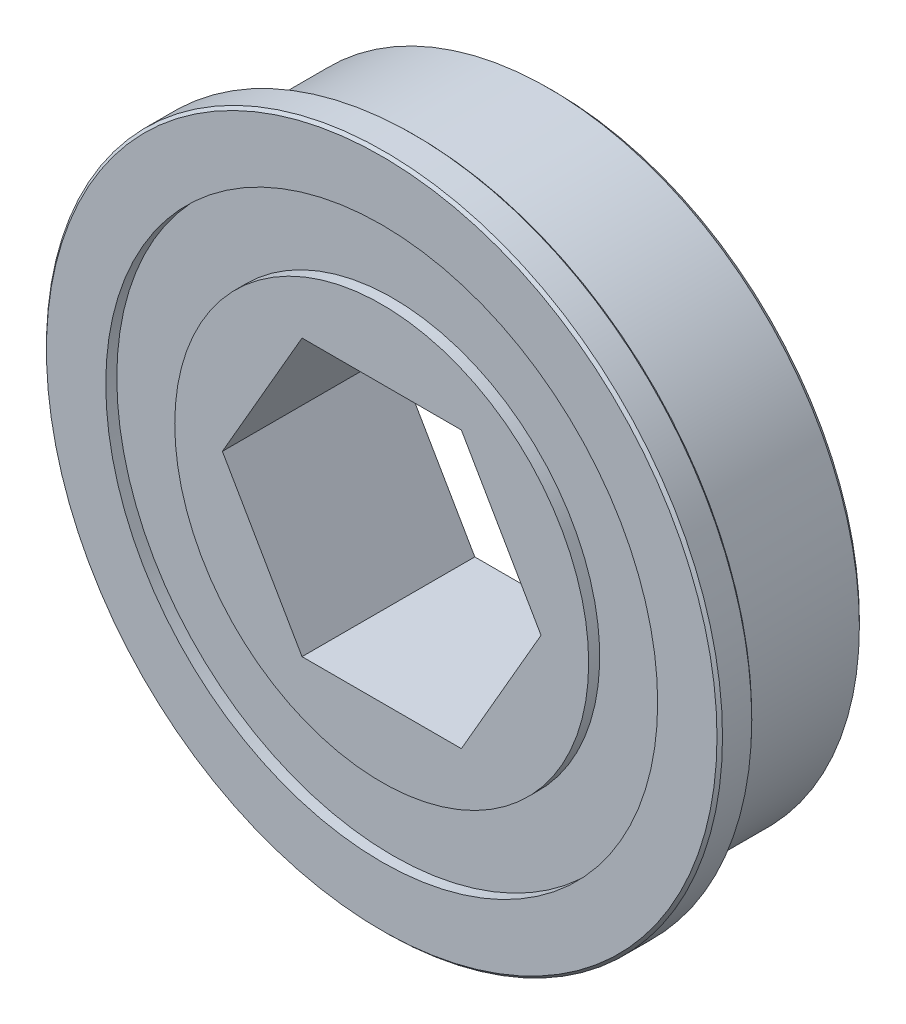
SolidWorks part; units mm, degrees
ref_plane "Front Plane" through (0, 0, 0) normal (0, 0, 1) x (1, 0, 0)
ref_plane "Top Plane" through (0, 0, 0) normal (0, 1, 0) x (1, 0, 0)
ref_plane "Right Plane" through (0, 0, 0) normal (1, 0, 0) x (0, 0, -1)
sketch "Sketch1" plane through (0, 0, 0) normal (0, 1, 0) x (1, 0, 0)
  line L0 (14.2875, 3.975) -> (0, 3.975)
  line L1 (0, 3.975) -> (0, -3.975)
  line L2 (0, -3.975) -> (15.5575, -3.975)
  line L3 (15.5575, -3.975) -> (15.5575, -2.375)
  line L4 (15.5575, -2.375) -> (14.1605, -2.375)
  line L5 (14.1605, -2.375) -> (14.1605, -2.121)
  line L6 (14.1605, -2.121) -> (14.2875, -2.121)
  line L7 (14.2875, -2.121) -> (14.2875, 3.975)
  line L8 (0, 3.975) -> (0, -3.975) construction
revolve "Revolve1" add sketch "Sketch1" angle 360 about L8
hole_wizard "1 (1) Diameter Hole1" positions "Sketch3" profile "Sketch2" hole size "1" standard "ANSI Inch"
sketch "Sketch3" plane through (0, 0, -3.975) normal (0, 0, -1) x (-1, 0, 0)
  point P0 (0, 0)
sketch "Sketch2" plane through (0, 0, -3.975) normal (1, 0, 0) x (0, 1, 0)
  line L0 (0, 0) -> (0, 0.508)
  line L1 (0, 0.508) -> (12.7, 0.508)
  line L2 (12.7, 0.508) -> (12.7, 0)
  line L5 (12.7, 0) -> (0, 0)
  line L10 (0, 0.508) -> (-12.7, 0.508) construction
  line L11 (0, -6.35) -> (0, 107.95) construction
  dimension "Hole Dia." = 25.4
  dimension "Hole Depth" = 0.508
  dimension "Drill Angle" = 180
sketch "Sketch4" plane through (0, 0, -3.467) normal (0, 0, -1) x (-1, 0, 0)
  circle A0 centre (0, 0) radius 9.525
extrude "Boss-Extrude1" add sketch "Sketch4" along normal blind 0.508
hole_wizard "1 (1) Diameter Hole2" positions "Sketch6" profile "Sketch5" hole size "1" standard "ANSI Inch"
sketch "Sketch6" plane through (0, 0, 3.975) normal (0, 0, 1) x (1, 0, 0)
  point P0 (0, 0)
sketch "Sketch5" plane through (0, 0, 3.975) normal (1, 0, 0) x (0, -1, 0)
  line L0 (0, 0) -> (0, 0.508)
  line L1 (0, 0.508) -> (12.7, 0.508)
  line L2 (12.7, 0.508) -> (12.7, 0)
  line L5 (12.7, 0) -> (0, 0)
  line L10 (0, 0.508) -> (-12.7, 0.508) construction
  line L11 (0, -6.35) -> (0, 107.95) construction
  dimension "Hole Dia." = 25.4
  dimension "Hole Depth" = 0.508
  dimension "Drill Angle" = 180
sketch "Sketch7" plane through (0, 0, 3.467) normal (0, 0, 1) x (1, 0, 0)
  circle A0 centre (0, 0) radius 9.525
extrude "Boss-Extrude2" add sketch "Sketch7" along normal blind 0.508
sketch "Sketch8" plane through (0, 0, 3.975) normal (0, 0, 1) x (1, 0, 0)
  line L0 (3.6662, 6.35) -> (-3.6662, 6.35)
  line L1 (-3.6662, 6.35) -> (-7.3323, 0)
  line L2 (-7.3323, 0) -> (-3.6662, -6.35)
  line L3 (-3.6662, -6.35) -> (3.6662, -6.35)
  line L4 (3.6662, -6.35) -> (7.3323, 0)
  line L5 (7.3323, 0) -> (3.6662, 6.35)
extrude "Cut-Extrude1" cut sketch "Sketch8" against normal through all
chamfer "Chamfer1" distance 0.127 angle 45 2 edges at (15.5575, 0, 3.975) (15.5575, 0, 2.375)
chamfer "Chamfer2" distance 0.254 angle 45 1 edges at (14.2875, 0, -3.975)
